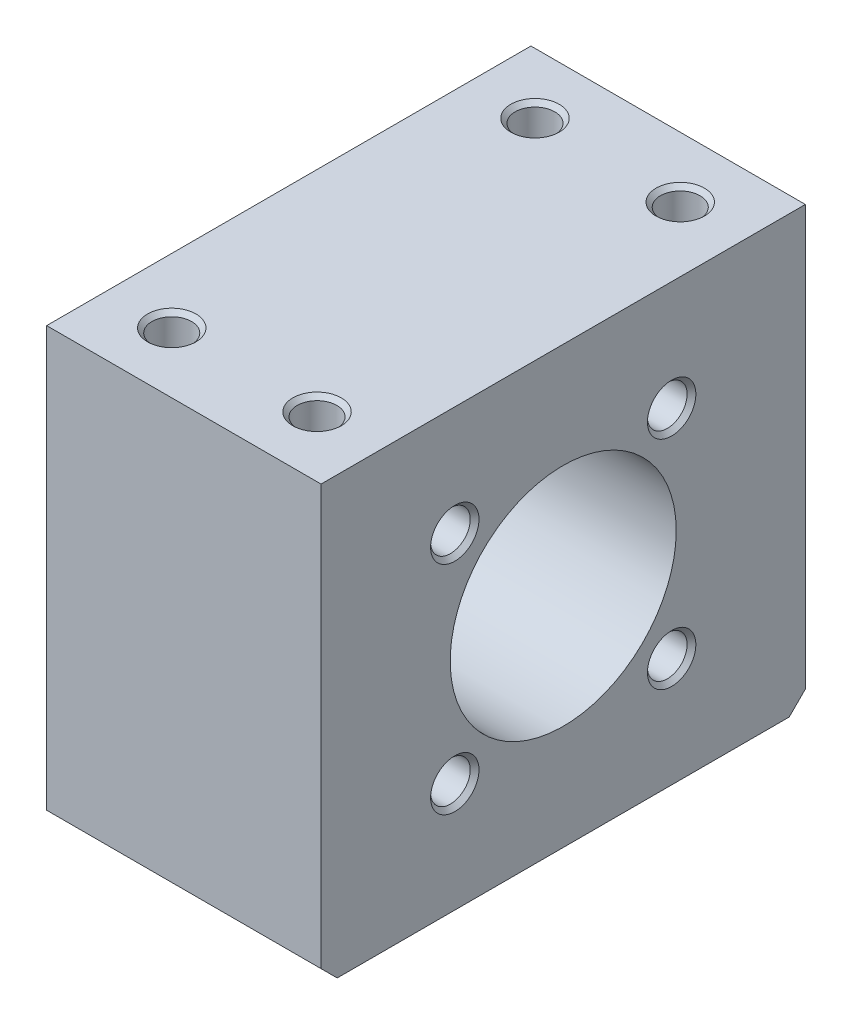
SolidWorks part; units mm, degrees
ref_plane "Piano frontale" through (0, 0, 0) normal (0, 0, 1) x (1, 0, 0)
ref_plane "Piano superiore" through (0, 0, 0) normal (0, 1, 0) x (1, 0, 0)
ref_plane "Piano destro" through (0, 0, 0) normal (1, 0, 0) x (0, 0, -1)
ref_plane "Piano1" through (17, 0, 0) normal (1, 0, 0) x (0, 0, -1)
sketch "Schizzo1" plane through (17, 0, 0) normal (1, 0, 0) x (0, 0, -1)
  line L0 (30, -27) -> (30, 27)
  line L1 (30, 27) -> (-30, 27)
  line L2 (-30, 27) -> (-30, -27)
  line L3 (-30, -27) -> (30, -27)
extrude "Estrusione-Estrusione1" add sketch "Schizzo1" against normal blind 34
hole_wizard "Foro per Vite M24-1" positions "Schizzo3" profile "Schizzo2" hole size "M24" standard "Ansi Metric"
sketch "Schizzo3" plane through (17, 0, 0) normal (1, 0, 0) x (0, 0, -1)
  point P0 (0, 0)
sketch "Schizzo2" plane through (17, 0, 0) normal (0, 1, 0) x (0, 0, -1)
  line L0 (0, 0) -> (0, 34)
  line L1 (0, 34) -> (14, 34)
  line L2 (14, 34) -> (14, 0)
  line L5 (14, 0) -> (0, 0)
  line L11 (0, -6.35) -> (0, 107.95) construction
  dimension "Thru Hole Dia." = 28
  dimension "Thru Hole Depth" = 34
hole_wizard "Foro1" positions "Schizzo5" profile "Schizzo4" legacy
sketch "Schizzo5" plane through (0, 27, 0) normal (0, 1, 0) x (1, 0, 0)
  point P0 (9, 22.5)
  point P1 (9, -22.5)
  point P2 (-9, 22.5)
  point P3 (-9, -22.5)
sketch "Schizzo4" plane through (9, 27, -22.5) normal (1, 0, 0) x (0, 0, 1)
  line L0 (0, 0) -> (0, 15.7321)
  line L1 (0, 15.7321) -> (2.4585, 14.3126)
  line L2 (2.4585, 14.3126) -> (2.4585, 0)
  line L4 (2.4585, 0) -> (0, 0)
  line L6 (0, 15.7321) -> (-2.4585, 14.3126) construction
  line L7 (0, -4.2442) -> (0, 117.3081) construction
  dimension "Diameter" = 4.917
  dimension "Depth" = 14.3126
  dimension "Drill Angle" = 120
hole_wizard "Foro2" positions "Schizzo7" profile "Schizzo6" legacy
sketch "Schizzo7" plane through (17, 0, 0) normal (1, 0, 0) x (0, 0, -1)
  point P0 (13.435, 13.435)
  point P1 (-13.435, -13.435)
  point P2 (13.435, -13.435)
  point P3 (-13.435, 13.435)
sketch "Schizzo6" plane through (17, 13.435, -13.435) normal (0, 1, 0) x (0, 0, -1)
  line L0 (0, 0) -> (0, 13.7321)
  line L1 (0, 13.7321) -> (2.4585, 12.3126)
  line L2 (2.4585, 12.3126) -> (2.4585, 0)
  line L4 (2.4585, 0) -> (0, 0)
  line L6 (0, 13.7321) -> (-2.4585, 12.3126) construction
  line L7 (0, -4.2442) -> (0, 117.3081) construction
  dimension "Diameter" = 4.917
  dimension "Depth" = 12.3126
  dimension "Drill Angle" = 120
chamfer "Smusso1" distance 0.5415 angle 45 8 edges at (-9, 27, 24.9585) (9, 27, 24.9585) (17, -13.435, 10.9765) (-9, 27, -20.0415) (17, -13.435, -15.8935) (17, 13.435, 10.9765) (17, 13.435, -15.8935) (9, 27, -20.0415)
chamfer "Smusso2" distance 2 angle 45 2 edges at (0, -27, 30) (0, -27, -30)
